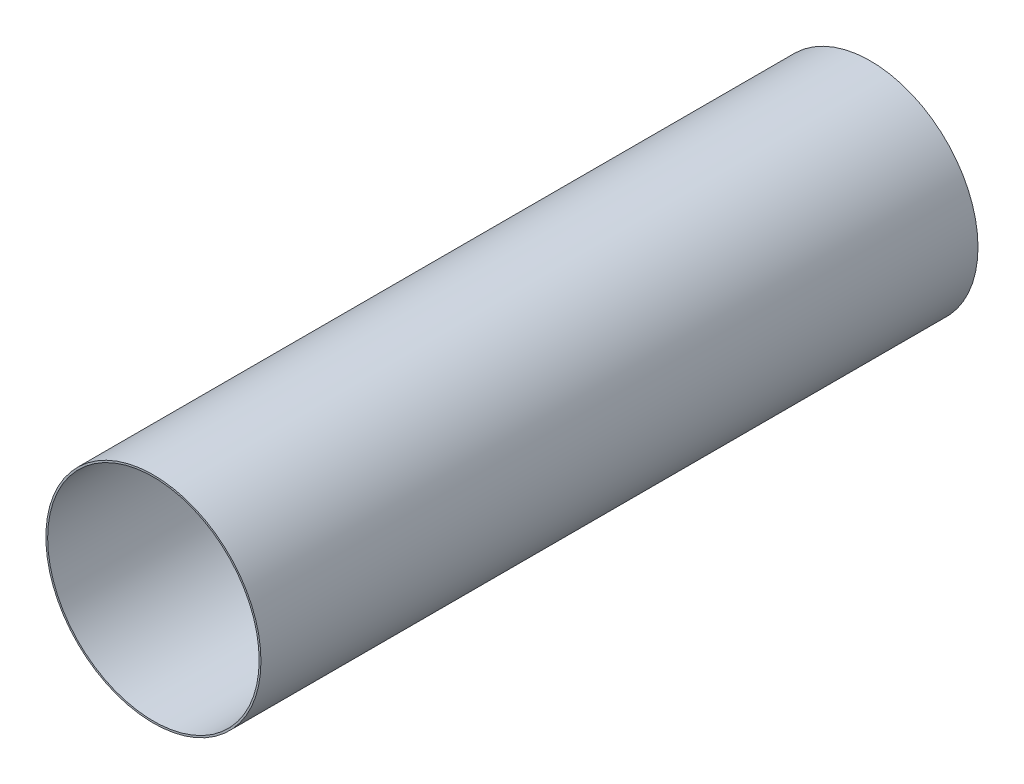
SolidWorks part; units mm, degrees
ref_plane "Front Plane" through (0, 0, 0) normal (0, 0, 1) x (1, 0, 0)
ref_plane "Top Plane" through (0, 0, 0) normal (0, 1, 0) x (1, 0, 0)
ref_plane "Right Plane" through (0, 0, 0) normal (1, 0, 0) x (0, 0, -1)
sketch "Sketch1" plane through (0, 0, 0) normal (0, 0, 1) x (1, 0, 0)
  circle A0 centre (0, 0) radius 30
  circle A1 centre (0, 0) radius 29.5
  dimension "D1" = 60
  dimension "D2" = 0.5
extrude "Boss-Extrude1" add sketch "Sketch1" along normal blind 200
